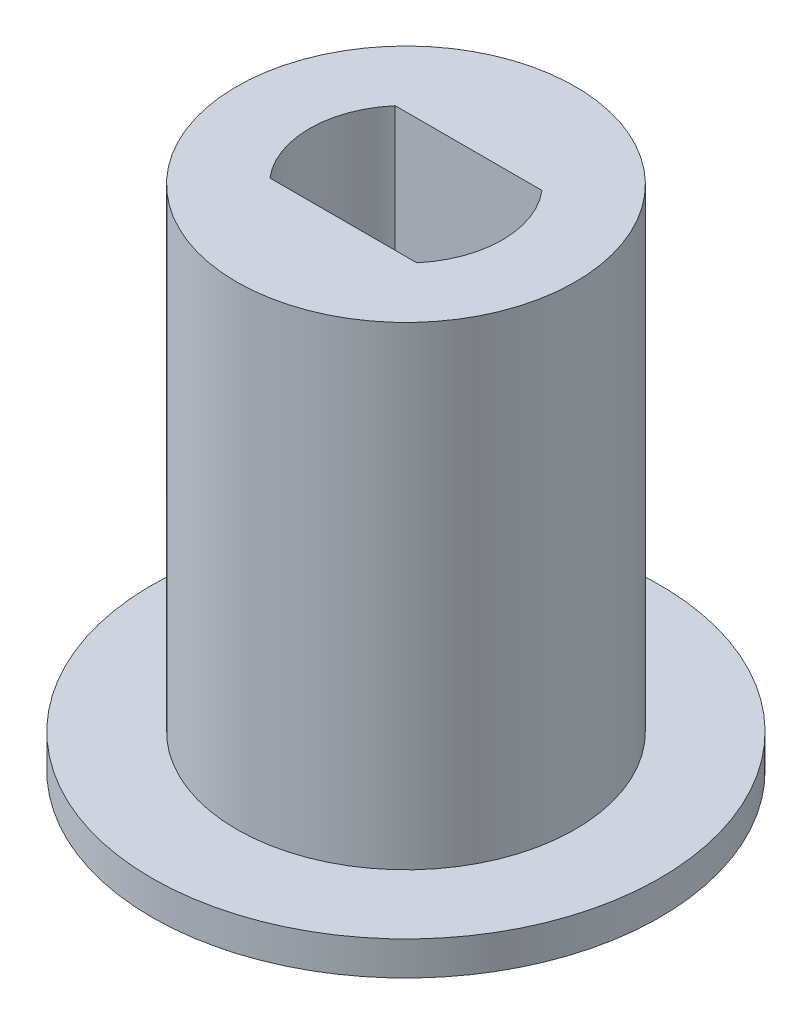
SolidWorks part; units mm, degrees
ref_plane "Front Plane" through (0, 0, 0) normal (0, 0, 1) x (1, 0, 0)
ref_plane "Top Plane" through (0, 0, 0) normal (0, 1, 0) x (1, 0, 0)
ref_plane "Right Plane" through (0, 0, 0) normal (1, 0, 0) x (0, 0, -1)
sketch "Sketch1" plane through (0, 0, 0) normal (0, 1, 0) x (1, 0, 0)
  circle A0 centre (0, 0) radius 10
extrude "Boss-Extrude2" add sketch "Sketch1" along normal blind 1
sketch "Sketch3" plane through (0, 1, 0) normal (0, 1, 0) x (1, 0, 0)
  circle A0 centre (0, 0) radius 5
extrude "Boss-Extrude3" add sketch "Sketch3" along normal blind 14
sketch "Sketch4" plane through (0, 15, 0) normal (0, 1, 0) x (1, 0, 0)
  line L0 (0, 0) -> (0, 2) construction
  line L1 (0, 2) -> (0, -2) construction
  line L3 (0, 2) -> (-4.3147, 2)
  line L4 (0, -2) -> (3.8775, -2)
  line L5 (0, -2) -> (0, 2)
  line L6 (0, 2) -> (3.8775, 2)
  line L7 (3.8775, -2) -> (3.8775, 2)
  line L8 (0, 2) -> (0, -2)
  line L9 (0, -2) -> (-4.3147, -2)
  line L10 (-4.3147, 2) -> (-4.3147, -2)
  circle A0 centre (0, 0) radius 3
extrude "Cut-Extrude1" cut sketch "Sketch4" against normal blind 19 contours L3 A0 L9 L5 | L4 A0 L6 L5
sketch "Sketch5" plane through (0, 1, 0) normal (0, 1, 0) x (1, 0, 0)
  circle A0 centre (0, 0) radius 12.5
extrude "Boss-Extrude4" add sketch "Sketch5" against normal up to surface (1 mm away) up to face at (0, 0, 0)
sketch "Sketch6" plane through (0, 1, 0) normal (0, 1, 0) x (1, 0, 0)
  line L4 (2.2361, 2) -> (-2.2361, 2)
  line L5 (-2.2361, -2) -> (2.2361, -2)
  line L6 (2.2361, 2) -> (-2.2361, 2)
  line L7 (-2.2361, -2) -> (2.2361, -2)
  arc A4 (-2.2361, 2) -> (-2.2361, -2) centre (0, 0) ccw
  arc A5 (2.2361, -2) -> (2.2361, 2) centre (0, 0) ccw
  arc A6 (-2.2361, 2) -> (-2.2361, -2) centre (0, 0) ccw
  arc A7 (2.2361, -2) -> (2.2361, 2) centre (0, 0) ccw
  dimension "D1" = 0
extrude "Cut-Extrude2" cut sketch "Sketch6" against normal blind 19
sketch "Sketch7" plane through (0, 15, 0) normal (0, 1, 0) x (1, 0, 0)
  line L4 (-2.2361, -2) -> (2.2361, -2)
  line L5 (2.2361, 2) -> (-2.2361, 2)
  line L6 (-2.2361, -2) -> (2.2361, -2)
  line L7 (2.2361, 2) -> (-2.2361, 2)
  circle A2 centre (0, 0) radius 5
  circle A3 centre (0, 0) radius 5
  arc A7 (2.2361, -2) -> (2.2361, 2) centre (0, 0) ccw
  arc A8 (-2.2361, 2) -> (-2.2361, -2) centre (0, 0) ccw
  arc A9 (2.2361, -2) -> (2.2361, 2) centre (0, 0) ccw
  arc A10 (-2.2361, 2) -> (-2.2361, -2) centre (0, 0) ccw
  dimension "D1" = 0
  dimension "D2" = 0
extrude "Boss-Extrude5" add sketch "Sketch7" along normal blind 2 separate body contours L6 A9 L7 A10
sketch "Sketch8" plane through (0, 17, 0) normal (0, 1, 0) x (1, 0, 0)
  circle A0 centre (0, 0) radius 7.5
extrude "Boss-Extrude6" add sketch "Sketch8" along normal blind 2
sketch "Sketch9" plane through (0, 19, 0) normal (0, 1, 0) x (1, 0, 0)
  circle A0 centre (0, 0) radius 1
extrude "Cut-Extrude3" cut sketch "Sketch9" against normal blind 25
sketch "Sketch10" plane through (0, 15, 0) normal (0, -1, 0) x (1, 0, 0)
  line L4 (-2.1213, -1.75) -> (2.1213, -1.75)
  line L5 (2.1213, 1.75) -> (-2.1213, 1.75)
  line L6 (-2.1213, -1.75) -> (2.1213, -1.75)
  line L7 (2.1213, 1.75) -> (-2.1213, 1.75)
  arc A4 (-2.1213, 1.75) -> (-2.1213, -1.75) centre (0, 0) ccw
  arc A5 (2.1213, -1.75) -> (2.1213, 1.75) centre (0, 0) ccw
  arc A6 (-2.1213, 1.75) -> (-2.1213, -1.75) centre (0, 0) ccw
  arc A7 (2.1213, -1.75) -> (2.1213, 1.75) centre (0, 0) ccw
  dimension "D1" = 0.25
extrude "Cut-Extrude4" cut sketch "Sketch10" against normal up to surface (2 mm away) up to face at (0, 17, 7.5)
sketch "Sketch11" plane through (0, 17, 0) normal (0, -1, 0) x (1, 0, 0)
  line L4 (-2.1213, -1.75) -> (2.1213, -1.75)
  line L5 (2.1213, 1.75) -> (-2.1213, 1.75)
  line L6 (-2.1213, -1.75) -> (2.1213, -1.75)
  line L7 (2.1213, 1.75) -> (-2.1213, 1.75)
  arc A4 (-2.1213, 1.75) -> (-2.1213, -1.75) centre (0, 0) ccw
  arc A5 (2.1213, -1.75) -> (2.1213, 1.75) centre (0, 0) ccw
  arc A6 (-2.1213, 1.75) -> (-2.1213, -1.75) centre (0, 0) ccw
  arc A7 (2.1213, -1.75) -> (2.1213, 1.75) centre (0, 0) ccw
  dimension "D1" = 0
extrude "Boss-Extrude7" add sketch "Sketch11" along normal blind 10
sketch "Sketch12" plane through (0, 0, 0) normal (0, -1, 0) x (1, 0, 0)
  circle A0 centre (0, 0) radius 4
  circle A3 centre (0, 0) radius 12.5
  circle A4 centre (0, 0) radius 12.5
  dimension "D1" = 0
sketch "Sketch14" plane through (0, 17, 0) normal (0, 1, 0) x (1, 0, 0)
  circle A2 centre (0, 0) radius 1
  circle A3 centre (0, 0) radius 1
  dimension "D1" = 0
extrude "Cut-Extrude5" cut sketch "Sketch14" against normal blind 18
sketch "Sketch15" plane through (0, 7, 0) normal (0, -1, 0) x (1, 0, 0)
  line L4 (-2.1213, -1.75) -> (2.1213, -1.75)
  line L5 (2.1213, 1.75) -> (-2.1213, 1.75)
  line L6 (-2.1213, -1.75) -> (2.1213, -1.75)
  line L7 (2.1213, 1.75) -> (-2.1213, 1.75)
  arc A4 (-2.1213, 1.75) -> (-2.1213, -1.75) centre (0, 0) ccw
  arc A5 (2.1213, -1.75) -> (2.1213, 1.75) centre (0, 0) ccw
  arc A6 (-2.1213, 1.75) -> (-2.1213, -1.75) centre (0, 0) ccw
  arc A7 (2.1213, -1.75) -> (2.1213, 1.75) centre (0, 0) ccw
  circle A8 centre (0, 0) radius 1
  circle A9 centre (0, 0) radius 1
  dimension "D1" = 0
  dimension "D2" = 0
extrude "Boss-Extrude8" add sketch "Sketch15" against normal blind 17
sketch "Sketch16" plane through (0, 7, 0) normal (0, -1, 0) x (1, 0, 0)
  line L4 (-2.1213, -1.75) -> (2.1213, -1.75)
  line L5 (2.1213, 1.75) -> (-2.1213, 1.75)
  line L6 (-2.1213, -1.75) -> (2.1213, -1.75)
  line L7 (2.1213, 1.75) -> (-2.1213, 1.75)
  arc A4 (-2.1213, 1.75) -> (-2.1213, -1.75) centre (0, 0) ccw
  arc A5 (2.1213, -1.75) -> (2.1213, 1.75) centre (0, 0) ccw
  arc A6 (-2.1213, 1.75) -> (-2.1213, -1.75) centre (0, 0) ccw
  arc A7 (2.1213, -1.75) -> (2.1213, 1.75) centre (0, 0) ccw
  circle A8 centre (0, 0) radius 1
  circle A9 centre (0, 0) radius 1
  dimension "D1" = 0
  dimension "D2" = 0
extrude "Cut-Extrude7" cut sketch "Sketch16" against normal up to surface (10 mm away) up to face at (0, 17, 7.5)
sketch "Sketch17" plane through (0, 15, 0) normal (0, -1, 0) x (1, 0, 0)
  line L4 (-2.2361, -2) -> (2.2361, -2)
  line L5 (2.2361, 2) -> (-2.2361, 2)
  line L6 (-2.2361, -2) -> (2.2361, -2)
  line L7 (2.2361, 2) -> (-2.2361, 2)
  arc A4 (-2.2361, 2) -> (-2.2361, -2) centre (0, 0) ccw
  arc A5 (2.2361, -2) -> (2.2361, 2) centre (0, 0) ccw
  arc A6 (-2.2361, 2) -> (-2.2361, -2) centre (0, 0) ccw
  arc A7 (2.2361, -2) -> (2.2361, 2) centre (0, 0) ccw
  dimension "D1" = 0
extrude "Cut-Extrude8" cut sketch "Sketch17" against normal up to surface (2 mm away) up to face at (0, 17, 7.5)
sketch "Sketch18" plane through (0, 17, 0) normal (0, -1, 0) x (1, 0, 0)
  circle A2 centre (0, 0) radius 7.5
  circle A3 centre (0, 0) radius 7.5
  dimension "D1" = 0
extrude "Boss-Extrude9" add sketch "Sketch18" along normal blind 1.75
sketch "Sketch19" plane through (0, 19, 0) normal (0, 1, 0) x (1, 0, 0)
  line L9 (2.1213, 1.75) -> (-2.1213, 1.75)
  line L10 (-2.1213, -1.75) -> (2.1213, -1.75)
  line L11 (2.1213, 1.75) -> (-2.1213, 1.75)
  line L12 (-2.1213, -1.75) -> (2.1213, -1.75)
  circle A0 centre (0, 0) radius 6.5
  circle A2 centre (0, 0) radius 7.5
  circle A3 centre (0, 0) radius 7.5
  arc A11 (-2.1213, 1.75) -> (-2.1213, -1.75) centre (0, 0) ccw
  arc A12 (2.1213, -1.75) -> (2.1213, 1.75) centre (0, 0) ccw
  arc A13 (-2.1213, 1.75) -> (-2.1213, -1.75) centre (0, 0) ccw
  arc A14 (2.1213, -1.75) -> (2.1213, 1.75) centre (0, 0) ccw
  arc M7 (-2.1213, -1.75) -> (-2.1213, 1.75) centre (0, 0) cw
  line M8 (-2.1213, 1.75) -> (2.1213, 1.75)
  arc M9 (2.1213, 1.75) -> (2.1213, -1.75) centre (0, 0) cw
  line M10 (2.1213, -1.75) -> (-2.1213, -1.75)
  circle M11 centre (0, 0) radius 7.5
  dimension "D1" = 0
  dimension "D2" = 1
  dimension "D3" = 0
extrude "Cut-Extrude9" cut sketch "Sketch19" against normal blind 1.75 contours A0 M11 | A0 M10 M7 M8 M9
sketch "Sketch22" plane through (0, 0, 0) normal (0, -1, 0) x (1, 0, 0)
  line L6 (-2.1679, -1.85) -> (2.1679, -1.85)
  line L7 (2.1679, 1.85) -> (-2.1679, 1.85)
  line L8 (-2.1679, -1.85) -> (2.1679, -1.85)
  line L9 (2.1679, 1.85) -> (-2.1679, 1.85)
  line L14 (-2.2361, -2) -> (2.2361, -2)
  line L15 (2.2361, 2) -> (-2.2361, 2)
  line L16 (-2.2361, -2) -> (2.2361, -2)
  line L17 (2.2361, 2) -> (-2.2361, 2)
  circle A2 centre (0, 0) radius 12.5
  circle A3 centre (0, 0) radius 12.5
  arc A11 (-2.1679, 1.85) -> (-2.1679, -1.85) centre (0, 0) ccw
  arc A12 (2.1679, -1.85) -> (2.1679, 1.85) centre (0, 0) ccw
  arc A13 (-2.1679, 1.85) -> (-2.1679, -1.85) centre (0, 0) ccw
  arc A14 (2.1679, -1.85) -> (2.1679, 1.85) centre (0, 0) ccw
  circle A15 centre (0, 0) radius 7.65
  circle A16 centre (0, 0) radius 7.65
  arc A24 (2.2361, -2) -> (2.2361, 2) centre (0, 0) ccw
  arc A25 (-2.2361, 2) -> (-2.2361, -2) centre (0, 0) ccw
  arc A26 (2.2361, -2) -> (2.2361, 2) centre (0, 0) ccw
  arc A27 (-2.2361, 2) -> (-2.2361, -2) centre (0, 0) ccw
  line M11 (-2.2361, 2) -> (2.2361, 2)
  arc M12 (2.2361, 2) -> (2.2361, -2) centre (0, 0) cw
  line M13 (2.2361, -2) -> (-2.2361, -2)
  arc M14 (-2.2361, -2) -> (-2.2361, 2) centre (0, 0) cw
  dimension "D1" = 0
  dimension "D2" = 0.15
  dimension "D3" = 0.15
  dimension "D4" = 0
extrude "Boss-Extrude11" add sketch "Sketch22" against normal up to surface (15 mm away) contours A14 L8 A13 L9 M11 M14 M13 M12 up to face at (0, 15, 0)
sketch "Sketch23" plane through (0, 24, 0) normal (0, 1, 0) x (1, 0, 0)
  circle A2 centre (0, 0) radius 1
  circle A3 centre (0, 0) radius 1
  dimension "D1" = 0
extrude "Cut-Extrude10" cut sketch "Sketch23" against normal up to surface (8.75 mm away) up to face at (0, 15.25, -7.5)
sketch "Sketch24" plane through (0, 1, 0) normal (0, 1, 0) x (1, 0, 0)
  circle A2 centre (0, 0) radius 7.5
  circle A3 centre (0, 0) radius 7.5
  circle A5 centre (0, 0) radius 12.5
  circle A6 centre (0, 0) radius 12.5
  dimension "D1" = 5
  dimension "D2" = 0
extrude "Cut-Extrude11" cut sketch "Sketch24" against normal blind 10
sketch "Sketch25" plane through (0, 15.25, 0) normal (0, -1, 0) x (1, 0, 0)
  circle A2 centre (0, 0) radius 7.5
  circle A3 centre (0, 0) radius 7.5
  dimension "D1" = 0
extrude "Cut-Extrude12" cut sketch "Sketch25" against normal blind 10
